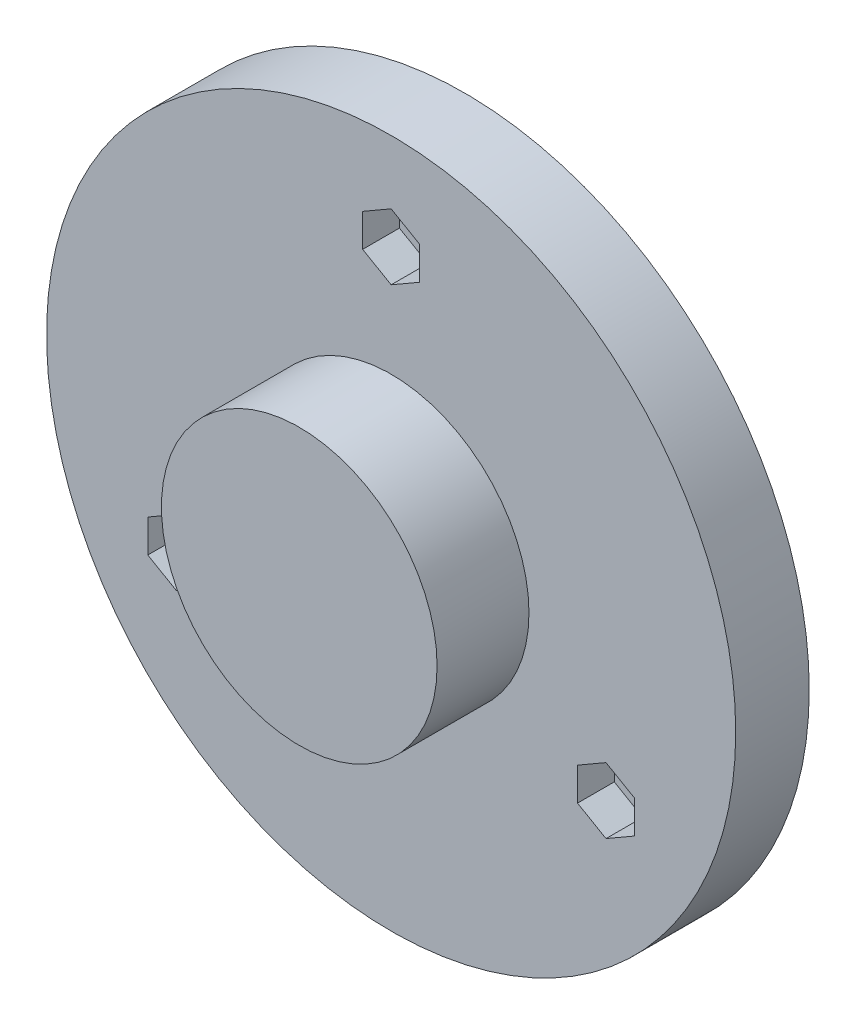
SolidWorks part; units mm, degrees
ref_plane "Front Plane" through (0, 0, 0) normal (0, 0, 1) x (1, 0, 0)
ref_plane "Top Plane" through (0, 0, 0) normal (0, 1, 0) x (1, 0, 0)
ref_plane "Right Plane" through (0, 0, 0) normal (1, 0, 0) x (0, 0, -1)
sketch "Sketch2" plane through (0, 0, 0) normal (0, 0, 1) x (1, 0, 0)
  circle A0 centre (0, 0) radius 37.5
  dimension "D1" = 75
extrude "Boss-Extrude1" add sketch "Sketch2" along normal blind 8
sketch "Sketch3" plane through (0, 0, 8) normal (0, 0, 1) x (1, 0, 0)
  line L1 (0, 23.42) -> (3.1004, 25.21)
  line L2 (3.1004, 25.21) -> (3.1004, 28.79)
  line L3 (3.1004, 28.79) -> (0, 30.58)
  line L4 (0, 30.58) -> (-3.1004, 28.79)
  line L5 (-3.1004, 28.79) -> (-3.1004, 25.21)
  line L6 (-3.1004, 25.21) -> (0, 23.42)
  circle A0 centre (0, 27) radius 3.1004 construction
  point P1 (0, 0)
  dimension "D1" = 3.58
  dimension "D2" = 27
extrude "Cut-Extrude1" cut sketch "Sketch3" against normal blind 4
pattern_circular "CirPattern1" count 3 over 360 about axis through (0, 0, 0) along (0, 0, 1) of "Cut-Extrude1"
sketch "Sketch5" plane through (0, 0, 4) normal (0, 0, 1) x (1, 0, 0)
  line L0 (-3.1004, 25.21) -> (3.1004, 28.79)
  circle A0 centre (0, 27) radius 1.75
  dimension "D1" = 3.5
extrude "Cut-Extrude2" cut sketch "Sketch5" against normal blind 17 contours L0 A0 | L0 A0
pattern_circular "CirPattern2" count 3 over 360 about axis through (0, 0, 0) along (0, 0, 1) of "Cut-Extrude2"
sketch "Sketch6" plane through (0, 0, 8) normal (0, 0, 1) x (1, 0, 0)
  circle A0 centre (0, 0) radius 15
  dimension "D1" = 30
extrude "Boss-Extrude2" add sketch "Sketch6" along normal blind 10
